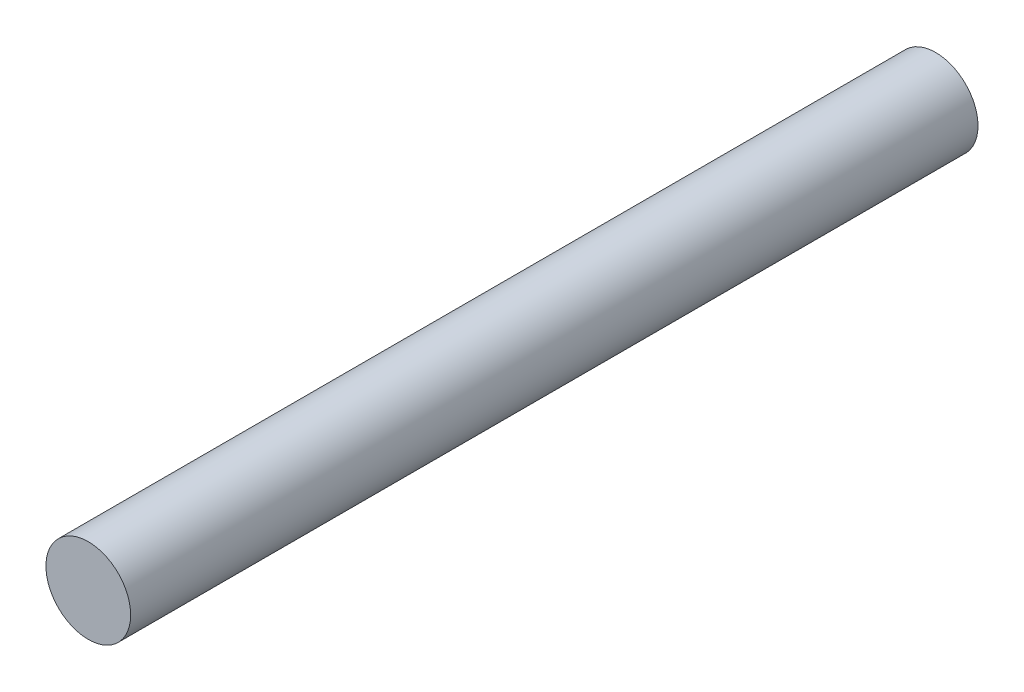
SolidWorks part; units mm, degrees
material "LW-PLA"
ref_plane "Front Plane" through (0, 0, 0) normal (0, 0, 1) x (1, 0, 0)
ref_plane "Top Plane" through (0, 0, 0) normal (0, 1, 0) x (1, 0, 0)
ref_plane "Right Plane" through (0, 0, 0) normal (1, 0, 0) x (0, 0, -1)
sketch "Sketch1" plane through (0, 0, 0) normal (0, 0, 1) x (1, 0, 0)
  circle A0 centre (0, 0) radius 0.75
  dimension "D1" = 1.5
extrude "Boss-Extrude1" add sketch "Sketch1" along normal blind 15
